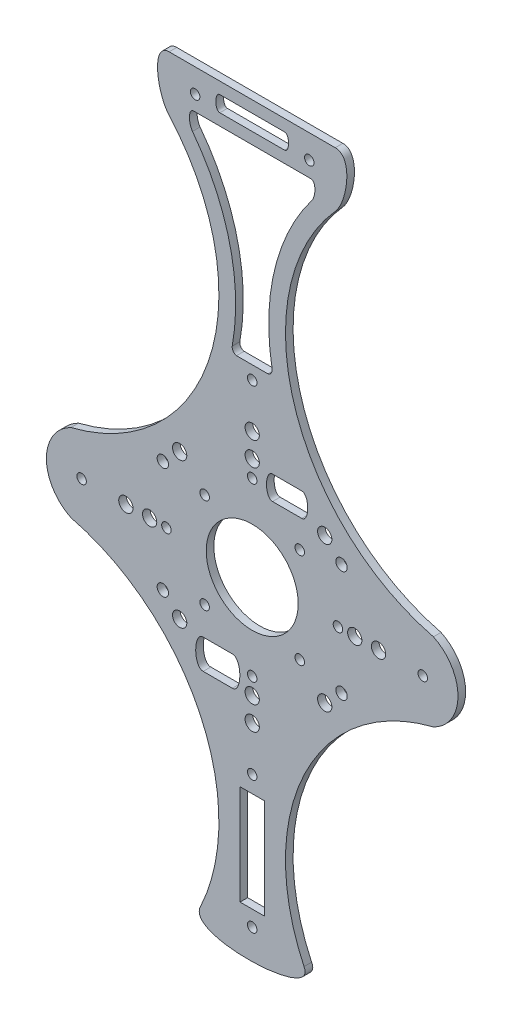
SolidWorks part; units mm, degrees
ref_plane "前视基准面" through (0, 0, 0) normal (0, 0, 1) x (1, 0, 0)
ref_plane "上视基准面" through (0, 0, 0) normal (0, 1, 0) x (1, 0, 0)
ref_plane "右视基准面" through (0, 0, 0) normal (1, 0, 0) x (0, 0, -1)
sketch "Model" plane through (0, 0, 0) normal (0, 0, 1) x (1, 0, 0)
  line L0 (164.2499, 187.0888) -> (146.7872, 187.0888)
  line L1 (159.067, 178.8832) -> (146.7872, 178.8832)
  line L2 (150.0887, 138.8371) -> (146.7872, 138.8371)
  line L3 (143.4857, 138.8371) -> (146.7872, 138.8371)
  line L4 (134.5074, 178.8832) -> (146.7872, 178.8832)
  line L5 (151.0532, 121.0703) -> (157.2092, 121.0703)
  line L6 (151.0532, 116.067) -> (157.2092, 116.067)
  line L7 (136.47, 84.0904) -> (142.626, 84.0904)
  line L8 (136.47, 77.8479) -> (142.626, 77.8479)
  line L9 (139.9743, 181.3177) -> (153.6002, 181.3177)
  line L10 (139.9743, 184.6313) -> (153.6002, 184.6313)
  line L11 (129.3246, 187.0888) -> (146.7872, 187.0888)
  line L12 (149.3414, 60.7179) -> (149.3414, 39.7179)
  line L13 (144.233, 60.7179) -> (144.233, 39.7179)
  line L14 (144.233, 39.7179) -> (149.3414, 39.7179)
  line L15 (144.233, 60.7179) -> (149.3414, 60.7179)
  circle A0 centre (156.7872, 110.1398) radius 1
  circle A1 centre (136.7872, 110.1398) radius 1
  circle A2 centre (136.7872, 90.1398) radius 1
  circle A3 centre (156.7872, 90.1398) radius 1
  circle A4 centre (168.354, 100.1398) radius 1.5
  circle A5 centre (146.7872, 121.7066) radius 1.5
  circle A6 centre (125.2205, 100.1398) radius 1.5
  circle A7 centre (146.7872, 78.5731) radius 1.5
  circle A8 centre (146.7872, 126.7066) radius 1.5
  circle A9 centre (120.2205, 100.1398) radius 1.5
  circle A10 centre (146.7872, 73.5731) radius 1.5
  circle A11 centre (173.354, 100.1398) radius 1.5
  circle A12 centre (146.7872, 118.171) radius 1
  circle A13 centre (128.756, 100.1398) radius 1
  circle A14 centre (146.7872, 82.1086) radius 1
  circle A15 centre (164.8184, 100.1398) radius 1
  circle A16 centre (162.0372, 115.3898) radius 1.5
  circle A17 centre (131.5372, 115.3898) radius 1.5
  circle A18 centre (131.5372, 84.8898) radius 1.5
  circle A19 centre (162.0372, 84.8898) radius 1.5
  circle A20 centre (182.6572, 100.1398) radius 1
  circle A21 centre (146.7872, 136.0369) radius 1
  circle A22 centre (110.9172, 100.1398) radius 1
  circle A23 centre (146.7872, 64.2428) radius 1
  arc A24 (184.891, 91.9296) -> (184.891, 108.3501) centre (180.9546, 100.1398) ccw
  arc A25 (108.6834, 108.3501) -> (108.6834, 91.9296) centre (112.6199, 100.1398) ccw
  circle A26 centre (146.7872, 36.4198) radius 1
  arc A27 (165.7942, 119.1469) -> (184.891, 108.3501) centre (194.7856, 148.1382) ccw
  arc A28 (164.2499, 175.4982) -> (165.7942, 119.1469) centre (194.7856, 148.1382) ccw
  arc A29 (108.6834, 108.3501) -> (127.7802, 119.1469) centre (98.7888, 148.1382) ccw
  arc A30 (127.7802, 81.1328) -> (108.6834, 91.9296) centre (98.7888, 52.1414) ccw
  arc A31 (165.7942, 81.1328) -> (157.6831, 34.6943) centre (194.7856, 52.1414) ccw
  arc A32 (184.891, 91.9296) -> (165.7942, 81.1328) centre (194.7856, 52.1414) ccw
  arc A33 (135.8914, 34.6943) -> (127.7802, 81.1328) centre (98.7888, 52.1414) ccw
  circle A34 centre (158.7872, 182.0998) radius 1
  circle A35 centre (134.7872, 182.0998) radius 1
  arc A36 (142.5873, 140.124) -> (134.2278, 175.0542) centre (98.8103, 148.1127) ccw
  arc A37 (159.3466, 175.0542) -> (150.9871, 140.124) centre (194.7642, 148.1127) ccw
  circle A38 centre (128.0017, 111.8543) radius 1.2
  circle A39 centre (165.5728, 111.8543) radius 1.2
  circle A40 centre (128.0017, 88.4254) radius 1.2
  circle A41 centre (165.5728, 88.4254) radius 1.2
  circle A42 centre (146.7872, 100.1398) radius 9.6721
  arc A43 (127.7802, 119.1469) -> (129.3246, 175.4982) centre (98.7888, 148.1382) ccw
  spline S0 degree 3 poles (0, 0) (0.3333, 0) (0.6667, 0) (1, 0) knots 0 0 0 0 1 1 1 1
  spline S1 degree 3 poles (0, 0) (0.3333, 0) (0.6667, 0) (1, 0) knots 0 0 0 0 1 1 1 1
  spline S2 degree 3 poles (135.8914, 34.6943) (132.8003, 28.1209) (160.7742, 29.1209) (157.6831, 34.6943) knots 0 0 0 0 21.791721 21.791721 21.791721 21.791721
  spline S3 degree 3 poles (150.9871, 140.124) (151.081, 139.6093) (150.6119, 138.8371) (150.0887, 138.8371) knots 0 0 0 0 1.569452 1.569452 1.569452 1.569452
  spline S4 degree 3 poles (142.5873, 140.124) (142.4934, 139.6093) (142.9626, 138.8371) (143.4857, 138.8371) knots 0 0 0 0 1.569452 1.569452 1.569452 1.569452
  spline S5 degree 3 poles (159.067, 178.8832) (160.3467, 178.8832) (160.1214, 176.0727) (159.3466, 175.0542) knots 0 0 0 0 3.839142 3.839142 3.839142 3.839142
  spline S6 degree 3 poles (134.5074, 178.8832) (133.2277, 178.8832) (133.4531, 176.0727) (134.2278, 175.0542) knots 0 0 0 0 3.839142 3.839142 3.839142 3.839142
  spline S7 degree 3 poles (136.47, 84.0904) (134.3892, 84.0904) (134.3892, 77.8479) (136.47, 77.8479) knots 0 0 0 0 6.242464 6.242464 6.242464 6.242464
  spline S8 degree 3 poles (142.626, 84.0904) (144.7068, 84.0904) (144.7068, 77.8479) (142.626, 77.8479) knots 0 0 0 0 6.242464 6.242464 6.242464 6.242464
  spline S9 degree 3 poles (0, 0) (0.3333, 0) (0.6667, 0) (1, 0) knots 0 0 0 0 1 1 1 1
  spline S10 degree 3 poles (157.2092, 121.0703) (158.877, 121.0703) (158.877, 116.067) (157.2092, 116.067) knots 0 0 0 0 5.0033 5.0033 5.0033 5.0033
  spline S11 degree 3 poles (151.0532, 121.0703) (149.3854, 121.0703) (149.3854, 116.067) (151.0532, 116.067) knots 0 0 0 0 5.0033 5.0033 5.0033 5.0033
  spline S12 degree 3 poles (139.9743, 184.6313) (138.8698, 184.6313) (138.8698, 181.3177) (139.9743, 181.3177) knots 0 0 0 0 3.313543 3.313543 3.313543 3.313543
  spline S13 degree 3 poles (153.6002, 184.6313) (154.7047, 184.6313) (154.7047, 181.3177) (153.6002, 181.3177) knots 0 0 0 0 3.313543 3.313543 3.313543 3.313543
  spline S14 degree 3 poles (164.2499, 187.0888) (168.1134, 187.0888) (166.8281, 178.3756) (164.2499, 175.4982) knots 0 0 0 0 11.590604 11.590604 11.590604 11.590604
  spline S15 degree 3 poles (129.3246, 187.0888) (125.461, 187.0888) (126.7464, 178.3756) (129.3246, 175.4982) knots 0 0 0 0 11.590604 11.590604 11.590604 11.590604
extrude "凸台-拉伸1" add sketch "Model" along normal blind 1.6 contours L7 S8 L8 S7 | L1 L4 S6 A36 S4 L3 L2 S3 A37 S5 | A1 | A0 | L9 S13 L10 S12 | L5 S10 L6 S11 | L0 L11 S15 A43 A29 A25 A30 A33 S2 A31 A32 A24 A27 A28 S14 | A9 | A8 | A7 | A6 | A5 | A4 | A3 | A2 | A17 | A16 | A15 | A14 | A13 | A12 | A11 | A10 | A23 | A22 | A21 | A20 | A19 | A18 | A35 | A34 | A26 | A42 | A41 | A40 | A39 | A38 | L12 L14 L13 L15 | S0 S1 S9
